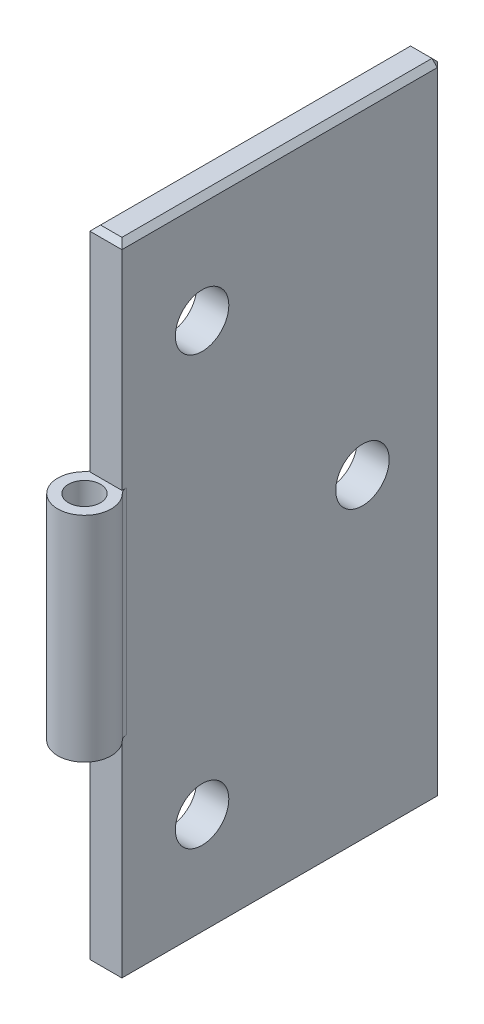
SolidWorks part; units mm, degrees
material "Brass"
ref_plane "Front Plane" through (0, 0, 0) normal (0, 0, 1) x (1, 0, 0)
ref_plane "Top Plane" through (0, 0, 0) normal (0, 1, 0) x (1, 0, 0)
ref_plane "Right Plane" through (0, 0, 0) normal (1, 0, 0) x (0, 0, -1)
sketch "Sketch1" plane through (0, 0, 0) normal (1, 0, 0) x (0, 0, -1)
  line L1 (15, -30) -> (-15, -30)
  line L2 (15, -30) -> (15, 30)
  line L3 (15, 30) -> (-15, 30)
  line L4 (-15, -30) -> (-15, 30)
  line L5 (15, -30) -> (-15, 30) construction
  line L6 (15, 30) -> (-15, -30) construction
  circle A0 centre (-7.5, 20) radius 2.5
  circle A1 centre (7.5, 0) radius 2.5
  circle A2 centre (-7.5, -20) radius 2.5
  point P0 (0, 0)
  point P12 (15, 0)
  dimension "D5" = 5
  dimension "D1" = 60
  dimension "D2" = 30
  dimension "D3" = 7.5
  dimension "D4" = 10
  dimension "D6" = 7.5
  dimension "D7" = 10
extrude "Boss-Extrude1" add sketch "Sketch1" along normal mid plane 3
sketch "Sketch3" plane through (0, 30, 0) normal (0, 1, 0) x (1, 0, 0)
  line L0 (-1.5, -15) -> (1.5, -15)
  arc A0 (-1.5, -15) -> (1.5, -15) centre (0, -17) ccw
  circle A1 centre (0, -17) radius 1.5
  dimension "D1" = 3
  dimension "D2" = 5
extrude "Boss-Extrude2" add sketch "Sketch3" against normal blind 20 from offset 20 offset against normal yes
fillet "Fillet2" radius 1 2 edges at (-1.5, 0, 15) (1.5, 0, 15)
chamfer "Chamfer2" distance 0.5 angle 45 10 edges at (0, -30, 15) (1.5, -30, 0) (-1.5, -30, 0) (0, -30, -15) (1.5, 0, -15) (-1.5, 0, -15) (0, 30, -15) (1.5, 30, 0) (0, 30, 15) (-1.5, 30, 0)
